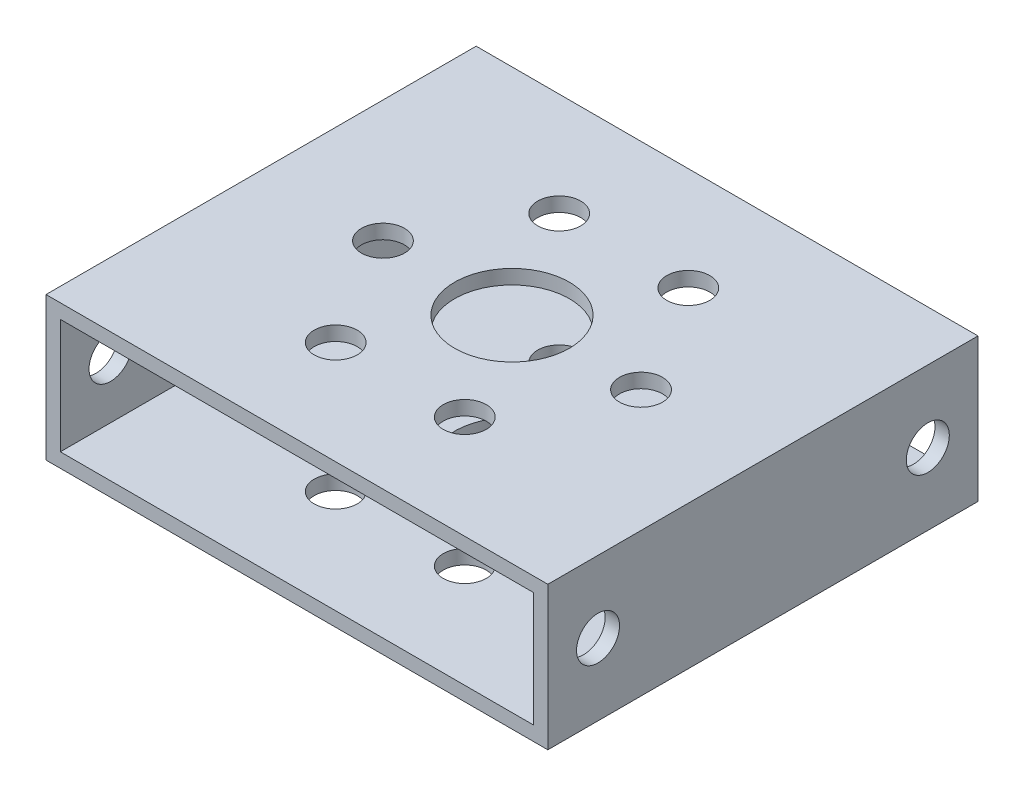
SolidWorks part; units mm, degrees
material "6063-T5"
ref_plane "前视基准面" through (0, 0, 0) normal (0, 0, 1) x (1, 0, 0)
ref_plane "上视基准面" through (0, 0, 0) normal (0, 1, 0) x (1, 0, 0)
ref_plane "右视基准面" through (0, 0, 0) normal (1, 0, 0) x (0, 0, -1)
sketch "草图1" plane through (0, 0, 0) normal (0, 0, 1) x (1, 0, 0)
  line L0 (-16.5, -4) -> (-16.5, 4)
  line L1 (-17.5, -5) -> (17.5, -5)
  line L2 (-17.5, -5) -> (-17.5, 5)
  line L3 (-17.5, 5) -> (17.5, 5)
  line L4 (17.5, -5) -> (17.5, 5)
  line L5 (-17.5, -5) -> (17.5, 5) construction
  line L6 (-17.5, 5) -> (17.5, -5) construction
  line L7 (-16.5, 4) -> (16.5, 4)
  line L8 (16.5, -4) -> (16.5, 4)
  line L9 (-16.5, -4) -> (16.5, -4)
  point P0 (0, 0)
  dimension "D1" = 10
  dimension "D2" = 35
  dimension "D3" = 1
extrude "凸台-拉伸1" add sketch "草图1" along normal mid plane 30
sketch "草图2" plane through (17.5, 0, 0) normal (1, 0, 0) x (0, 0, -1)
  line L0 (-11.5, 0) -> (11.5, 0) construction
  circle A0 centre (11.5, 0) radius 1.5
  circle A1 centre (-11.5, 0) radius 1.5
  point P4 (0, 0)
  dimension "D2" = 3
  dimension "D1" = 23
extrude "切除-拉伸1" cut sketch "草图2" against normal blind 50
sketch "草图3" plane through (0, 5, 0) normal (0, 1, 0) x (1, 0, 0)
  line L0 (-4.5, 7.7942) -> (0, 0) construction
  line L1 (0, 0) -> (0, 9) construction
  circle A0 centre (0, 0) radius 4
  circle A1 centre (0, 0) radius 9 construction
  circle A2 centre (-4.5, 7.7942) radius 1.5
  circle A3 centre (4.5, 7.7942) radius 1.5
  circle A4 centre (9, 0) radius 1.5
  circle A5 centre (4.5, -7.7942) radius 1.5
  circle A6 centre (-4.5, -7.7942) radius 1.5
  circle A7 centre (-9, 0) radius 1.5
  point P6 (-5.8922, -9.3225)
  point P8 (0, 0)
  point P19 (0, 0)
  dimension "D1" = 8
  dimension "D2" = 18
  dimension "D4" = 3
  dimension "D3" = 30
  dimension "D5" = 6
extrude "切除-拉伸2" cut sketch "草图3" against normal blind 10
